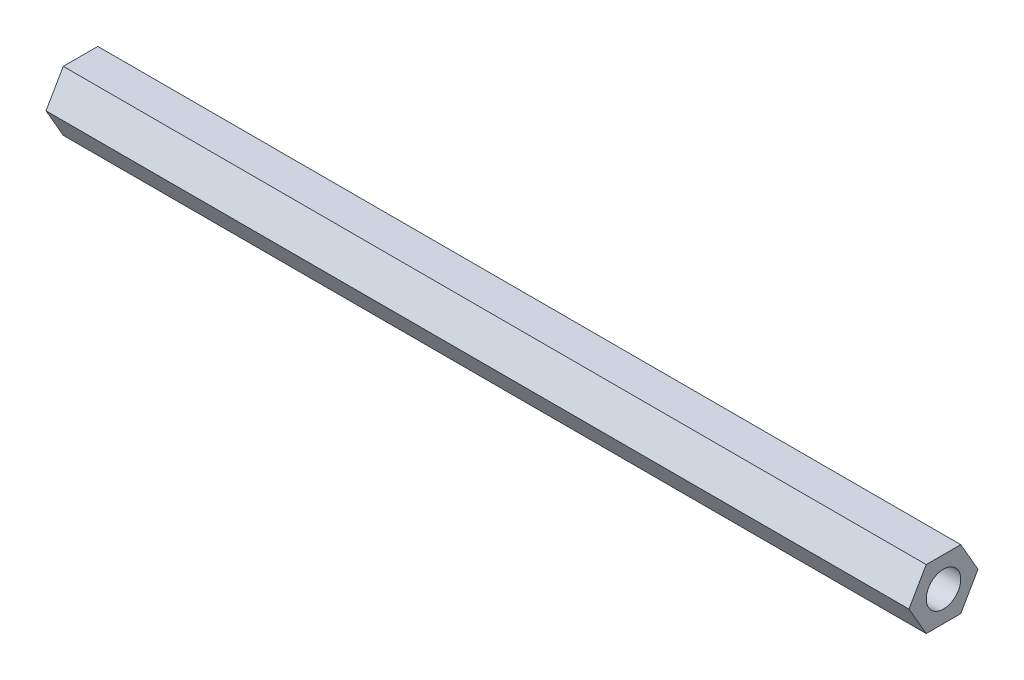
SolidWorks part; units mm, degrees
material "ABS"
ref_plane "Front Plane" through (0, 0, 0) normal (0, 0, 1) x (1, 0, 0)
ref_plane "Top Plane" through (0, 0, 0) normal (0, 1, 0) x (1, 0, 0)
ref_plane "Right Plane" through (0, 0, 0) normal (1, 0, 0) x (0, 0, -1)
sketch "Sketch1" plane through (0, 0, 0) normal (1, 0, 0) x (0, 0, -1)
  line L1 (1, 1.7321) -> (-1, 1.7321)
  line L2 (-1, 1.7321) -> (-2, 0)
  line L3 (-2, 0) -> (-1, -1.7321)
  line L4 (-1, -1.7321) -> (1, -1.7321)
  line L5 (1, -1.7321) -> (2, 0)
  line L6 (2, 0) -> (1, 1.7321)
  circle A0 centre (0, 0) radius 1.7321 construction
  circle A2 centre (0, 0) radius 1
  dimension "D2" = 2
  dimension "D1" = 4
extrude "Boss-Extrude1" add sketch "Sketch1" along normal blind 50
